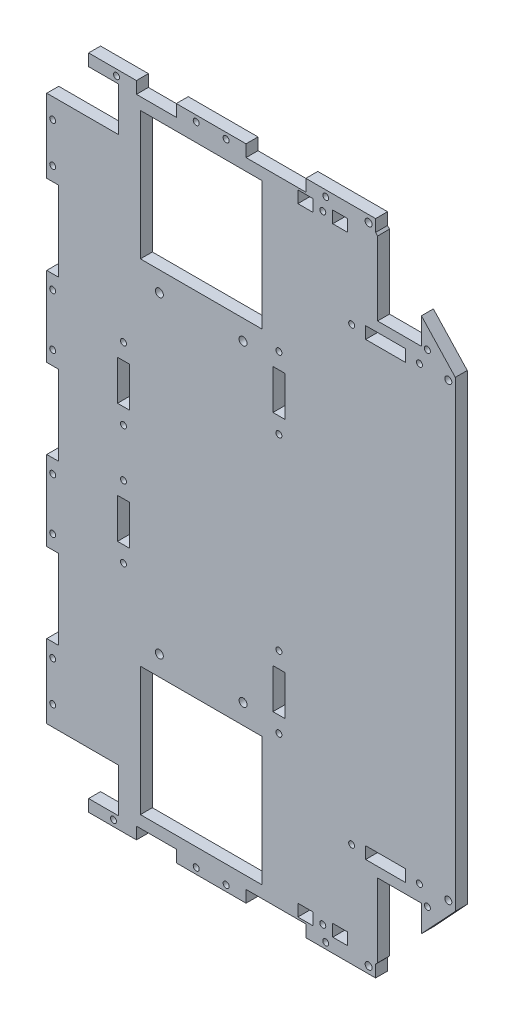
SolidWorks part; units mm, degrees
ref_plane "Plan de face" through (0, 0, 0) normal (0, 0, 1) x (1, 0, 0)
ref_plane "Plan de dessus" through (0, 0, 0) normal (0, 1, 0) x (1, 0, 0)
ref_plane "Plan de droite" through (0, 0, 0) normal (1, 0, 0) x (0, 0, -1)
sketch "Esquisse1" plane through (0, 0, 0) normal (0, 0, 1) x (1, 0, 0)
  line L1 (0, 0) -> (-205, 0)
  line L2 (0, 0) -> (0, 330)
  line L3 (0, 330) -> (-205, 330)
  line L4 (-205, 0) -> (-205, 330)
  dimension "D1" = 330
  dimension "D2" = 205
extrude "Boss.-Extru.1" add sketch "Esquisse1" along normal blind 6
sketch "Esquisse2" plane through (0, 0, 6) normal (0, 0, 1) x (1, 0, 0)
  line L0 (-205, 0) -> (0, 0) construction
  line L2 (-205, 0) -> (-156, 49) construction
  line L9 (0, 330) -> (-205, 330) construction
  line L10 (-205, 330) -> (-205, 0) construction
  line L12 (-205, 165) -> (0, 165) construction
  line L23 (0, 0) -> (0, 330) construction
  line L32 (-25, 275) -> (-45, 275)
  line L33 (-25, 275) -> (-25, 281)
  line L34 (-25, 281) -> (-45, 281)
  line L35 (-45, 275) -> (-45, 281)
  line L36 (-25, 49) -> (-45, 49)
  line L37 (-25, 49) -> (-25, 55)
  line L38 (-25, 55) -> (-45, 55)
  line L39 (-45, 49) -> (-45, 55)
  dimension "D26" = 25
  dimension "D9" = 135
  dimension "D25" = 20
  dimension "D29" = 49
  dimension "D30" = 6
  dimension "D49" = 20
  dimension "D50" = 6
  dimension "D51" = 25
  dimension "D52" = 49
extrude "roulement + encoche interne" cut sketch "Esquisse2" against normal through all
sketch "Esquisse3" plane through (0, 0, 6) normal (0, 0, 1) x (1, 0, 0)
  line L0 (0, 330) -> (-40, 330)
  line L1 (-40, 330) -> (-40, 324)
  line L2 (-40, 324) -> (0, 281)
  line L3 (-205, 0) -> (0, 0) construction
  line L4 (0, 281) -> (0, 330)
  line L5 (-40, 0) -> (-40, 6)
  line L6 (-40, 6) -> (0, 49)
  line L7 (0, 330) -> (-205, 330) construction
  line L8 (-205, 330) -> (-205, 0) construction
  line L9 (0, 0) -> (-40, 0)
  line L10 (0, 0) -> (0, 330) construction
  line L11 (0, 330) -> (-205, 330) construction
  line L12 (-75, 0) -> (-105, 0)
  line L13 (-75, 0) -> (-75, 6)
  line L14 (-205, 145) -> (-199, 145)
  line L15 (-205, 65) -> (-199, 65)
  line L16 (-205, 65) -> (-205, 105)
  line L17 (-205, 105) -> (-199, 105)
  line L18 (-199, 65) -> (-199, 105)
  line L19 (-205, 145) -> (-205, 185)
  line L20 (-205, 185) -> (-199, 185)
  line L21 (-75, 6) -> (-105, 6)
  line L22 (-105, 0) -> (-105, 6)
  line L23 (-75, 330) -> (-105, 330)
  line L24 (-75, 330) -> (-75, 324)
  line L25 (-75, 324) -> (-105, 324)
  line L26 (-105, 330) -> (-105, 324)
  line L27 (-205, 302) -> (-169, 302)
  line L28 (-199, 145) -> (-199, 185)
  line L29 (-205, 225) -> (-199, 225)
  line L30 (-205, 225) -> (-205, 265)
  line L31 (-205, 265) -> (-199, 265)
  line L32 (-199, 225) -> (-199, 265)
  line L33 (0, 49) -> (0, 0)
  line L34 (-140, 0) -> (-160, 0)
  line L35 (-140, 0) -> (-140, 6)
  line L36 (-140, 6) -> (-160, 6)
  line L37 (-205, 302) -> (-205, 330)
  line L38 (-160, 0) -> (-160, 6)
  line L39 (-140, 330) -> (-160, 330)
  line L40 (-140, 330) -> (-140, 324)
  line L41 (-140, 324) -> (-160, 324)
  line L42 (-160, 330) -> (-160, 324)
  line L43 (-184, 324) -> (-169, 324)
  line L44 (-169, 302) -> (-169, 324)
  line L46 (-205, 0) -> (-205, 28)
  line L47 (-184, 6) -> (-169, 6)
  line L49 (-205, 28) -> (-169, 28)
  line L50 (-169, 6) -> (-169, 28)
  line L51 (-205, 0) -> (-184, 0)
  line L52 (-205, 330) -> (-184, 330)
  line L54 (-184, 0) -> (-184, 6)
  line L56 (-184, 330) -> (-184, 324)
  dimension "D3" = 49
  dimension "D4" = 6
  dimension "D5" = 40
  dimension "D6" = 30
  dimension "D7" = 40
  dimension "D8" = 6
  dimension "D9" = 40
  dimension "D10" = 6
  dimension "D11" = 40
  dimension "D12" = 40
  dimension "D13" = 40
  dimension "D14" = 6
  dimension "D15" = 75
  dimension "D16" = 65
  dimension "D17" = 6
  dimension "D18" = 30
  dimension "D19" = 75
  dimension "D20" = 6
  dimension "D21" = 6
  dimension "D22" = 35
  dimension "D23" = 40
  dimension "D24" = 49
  dimension "D25" = 36
  dimension "D26" = 22
  dimension "D27" = 22
  dimension "D28" = 20
  dimension "D29" = 6
  dimension "D30" = 35
  dimension "D31" = 20
  dimension "D32" = 6
  dimension "D33" = 6
  dimension "D34" = 36
  dimension "D35" = 6
  dimension "D36" = 24
  dimension "D37" = 24
extrude "Enlèv. mat encoche" cut sketch "Esquisse3" against normal through all
sketch "Esquisse6" plane through (0, 0, 6) normal (0, 0, 1) x (1, 0, 0)
  line L0 (-199, 165) -> (0, 165) construction
  line L1 (-158, 253.5) -> (-158, 318)
  line L2 (-97, 318) -> (-97, 253.5)
  line L3 (-158, 253.5) -> (-97, 253.5)
  line L4 (-205, 225) -> (-205, 185) construction
  line L5 (-199, 145) -> (-199, 185) construction
  line L6 (0, 49) -> (0, 281) construction
  line L7 (-85.5, 90) -> (-85.5, 110)
  line L8 (-127.5, 250.9395) -> (-127.5, -49749.0605) construction
  line L9 (-40, 330) -> (-75, 330) construction
  line L10 (-158, 318) -> (-97, 318)
  line L11 (-91.5, 110) -> (-85.5, 110)
  line L12 (-91.5, 90) -> (-91.5, 110)
  line L13 (-91.5, 90) -> (-85.5, 90)
  line L14 (-163.5, 125) -> (-163.5, 145)
  line L15 (-169.5, 145) -> (-163.5, 145)
  line L16 (-169.5, 125) -> (-169.5, 145)
  line L17 (-169.5, 125) -> (-163.5, 125)
  line L18 (-158, 12) -> (-97, 12)
  line L19 (-158, 76.5) -> (-97, 76.5)
  line L20 (-97, 12) -> (-97, 76.5)
  line L21 (-158, 76.5) -> (-158, 12)
  line L22 (-169.5, 205) -> (-163.5, 205)
  line L23 (-169.5, 205) -> (-169.5, 185)
  line L24 (-169.5, 185) -> (-163.5, 185)
  line L25 (-163.5, 205) -> (-163.5, 185)
  line L26 (-91.5, 240) -> (-85.5, 240)
  line L27 (-91.5, 240) -> (-91.5, 220)
  line L28 (-91.5, 220) -> (-85.5, 220)
  line L29 (-85.5, 240) -> (-85.5, 220)
  line L30 (0, 49) -> (0, 281) construction
  line L31 (-205, 225) -> (-205, 185) construction
  line L32 (-105, 330) -> (-140, 330) construction
  circle A0 centre (-148.5, 243.5) radius 2
  circle A1 centre (-106.5, 243.5) radius 2
  circle A2 centre (-106.5, 86.5) radius 2
  circle A3 centre (-148.5, 86.5) radius 2
  point P19 (-127.5, 253.5)
  dimension "D4" = 4
  dimension "D5" = 78.5
  dimension "D6" = 64.5
  dimension "D3" = 30.5
  dimension "D7" = 42
  dimension "D8" = 10
  dimension "D9" = 77.5
  dimension "D15" = 20
  dimension "D16" = 90
  dimension "D17" = 85.5
  dimension "D18" = 6
  dimension "D19" = 20
  dimension "D20" = 6
  dimension "D21" = 35.5
  dimension "D22" = 125
extrude "bloc moteur" cut sketch "Esquisse6" against normal through all
sketch "Esquisse7" plane through (0, 0, 6) normal (0, 0, 1) x (1, 0, 0)
  line L0 (-140, 0) -> (-105, 0) construction
  line L1 (-205, 65) -> (-205, 28) construction
  line L2 (-40, 330) -> (-40, 324) construction
  line L3 (-75, 0) -> (-40, 0) construction
  line L4 (-163.5, 125) -> (-163.5, 145) construction
  line L5 (-40, 330) -> (-75, 330) construction
  line L6 (-205, 145) -> (-205, 105) construction
  line L7 (-199, 105) -> (-205, 105) construction
  line L8 (-205, 145) -> (-199, 145) construction
  line L9 (-205, 225) -> (-205, 185) construction
  line L10 (-199, 185) -> (-205, 185) construction
  line L11 (-205, 225) -> (-199, 225) construction
  line L12 (-205, 302) -> (-205, 265) construction
  line L13 (-199, 265) -> (-205, 265) construction
  line L14 (-105, 330) -> (-140, 330) construction
  line L15 (-205, 65) -> (-205, 28) construction
  line L16 (-45, 55) -> (-45, 49) construction
  line L17 (-45, 49) -> (-25, 49) construction
  line L18 (-25, 49) -> (-25, 55) construction
  line L19 (-75, 324) -> (-75, 330) construction
  line L20 (-40, 330) -> (-75, 330) construction
  line L21 (-205, 65) -> (-199, 65) construction
  line L22 (-25, 281) -> (-45, 281) construction
  line L23 (-45, 281) -> (-45, 275) construction
  line L24 (-45, 275) -> (-25, 275) construction
  line L25 (-25, 275) -> (-25, 281) construction
  line L26 (0, 49) -> (0, 281) construction
  line L27 (-45, 275) -> (-25, 275) construction
  line L28 (-45, 49) -> (-25, 49) construction
  line L29 (-75, 0) -> (-40, 0) construction
  line L30 (-40, 6) -> (-40, 0) construction
  line L31 (-75, 0) -> (-75, 6) construction
  line L32 (-85.5, 90) -> (-85.5, 110) construction
  line L33 (-199, 165) -> (0, 165) construction
  line L34 (-85.5, 110) -> (-91.5, 110) construction
  line L35 (-160, 330) -> (-160, 324) construction
  line L36 (-140, 324) -> (-140, 330) construction
  line L37 (-105, 330) -> (-105, 324) construction
  line L38 (-105, 6) -> (-105, 0) construction
  line L39 (-199, 145) -> (-199, 185) construction
  line L40 (0, 49) -> (0, 281) construction
  line L41 (-140, 0) -> (-140, 6) construction
  line L45 (-91.5, 90) -> (-85.5, 90) construction
  line L46 (-169.5, 125) -> (-163.5, 125) construction
  line L47 (-163.5, 145) -> (-169.5, 145) construction
  circle A0 centre (-65, 3) radius 1.5
  circle A1 centre (-171.5042, 3) radius 1.5
  circle A2 centre (-115, 3) radius 1.5
  circle A3 centre (-202, 58) radius 1.5
  circle A4 centre (-202, 272) radius 1.5
  circle A5 centre (-65, 327) radius 1.5
  circle A6 centre (-170, 327) radius 1.5
  circle A7 centre (-18, 52) radius 1.5
  circle A8 centre (-52, 52) radius 1.5
  circle A9 centre (-18, 278) radius 1.5
  circle A10 centre (-52, 278) radius 1.5
  circle A11 centre (-202, 112) radius 1.5
  circle A12 centre (-202, 138) radius 1.5
  circle A13 centre (-166.5, 117) radius 1.5
  circle A14 centre (-130, 327) radius 1.5
  circle A15 centre (-202, 192) radius 1.5
  circle A16 centre (-202, 218) radius 1.5
  circle A17 centre (-166.5, 153) radius 1.5
  circle A18 centre (-130, 3) radius 1.5
  circle A19 centre (-115, 327) radius 1.5
  circle A20 centre (-202, 292) radius 1.5
  circle A21 centre (-202, 38) radius 1.5
  circle A22 centre (-43.5, 326.5) radius 1.75
  circle A23 centre (-3.5, 278) radius 1.75
  circle A24 centre (-3.5, 52) radius 1.75
  circle A25 centre (-43.5, 3.5) radius 1.75
  circle A26 centre (-88.5, 82) radius 1.5
  circle A27 centre (-88.5, 118) radius 1.5
  circle A28 centre (-14, 44) radius 1.5
  circle A29 centre (-14, 286) radius 1.5
  circle A30 centre (-88.5, 212) radius 1.5
  circle A31 centre (-88.5, 248) radius 1.5
  circle A32 centre (-166.5, 177) radius 1.5
  circle A33 centre (-166.5, 213) radius 1.5
  point P71 (-25, 52)
  point P158 (-105, 3)
  dimension "D1" = 3
  dimension "D2" = 3
  dimension "D6" = 3
  dimension "D7" = 3
  dimension "D8" = 3
  dimension "D10" = 3
  dimension "D11" = 3
  dimension "D13" = 33.4958
  dimension "D14" = 3
  dimension "D15" = 10
  dimension "D16" = 3
  dimension "D17" = 3
  dimension "D18" = 7
  dimension "D19" = 3
  dimension "D20" = 3
  dimension "D21" = 7
  dimension "D22" = 3
  dimension "D23" = 3
  dimension "D24" = 7
  dimension "D25" = 3
  dimension "D26" = 3
  dimension "D27" = 7
  dimension "D28" = 3
  dimension "D29" = 3
  dimension "D30" = 7
  dimension "D31" = 3
  dimension "D32" = 3
  dimension "D33" = 7
  dimension "D34" = 10
  dimension "D35" = 3
  dimension "D36" = 3
  dimension "D37" = 3
  dimension "D38" = 7
  dimension "D39" = 3
  dimension "D40" = 3
  dimension "D41" = 3
  dimension "D42" = 7
  dimension "D43" = 3
  dimension "D44" = 10
  dimension "D45" = 3
  dimension "D46" = 3
  dimension "D47" = 3
  dimension "D48" = 8
  dimension "D49" = 3
  dimension "D50" = 10
  dimension "D51" = 3
  dimension "D52" = 3
  dimension "D53" = 3
  dimension "D55" = 3
  dimension "D56" = 3
  dimension "D57" = 7
  dimension "D58" = 3
  dimension "D59" = 20
  dimension "D60" = 3
  dimension "D61" = 3
  dimension "D62" = 10
  dimension "D63" = 3
  dimension "D64" = 3
  dimension "D65" = 20
  dimension "D66" = 3
  dimension "D67" = 3.5
  dimension "D68" = 3.5
  dimension "D69" = 3.5
  dimension "D70" = 3.5
  dimension "D71" = 3.5
  dimension "D73" = 3.5
  dimension "D74" = 3.5
  dimension "D75" = 3
  dimension "D76" = 3.5
  dimension "D77" = 3.5
  dimension "D78" = 3.5
  dimension "D79" = 3
  dimension "D81" = 3
  dimension "D82" = 3
  dimension "D84" = 3
  dimension "D85" = 3
  dimension "D86" = 8
  dimension "D87" = 3
  dimension "D88" = 3
  dimension "D89" = 14
  dimension "D91" = 3
  dimension "D90" = 5
  dimension "D92" = 14
  dimension "D93" = 5
  dimension "D80" = 8
  dimension "D83" = 8
  dimension "D94" = 10
  dimension "D12" = 10
  dimension "D54" = 7
  dimension "D72" = 3
extrude "Enlèv. mat.-Extru.4" cut sketch "Esquisse7" against normal through all
sketch "Esquisse8" plane through (0, 0, 0) normal (0, 0, -1) x (-1, 0, 0)
  line L1 (199, 165) -> (0, 165) construction
  line L4 (199, 145) -> (199, 185) construction
  line L5 (0, 49) -> (0, 281) construction
  circle A0 centre (14, 44) radius 2.995
  circle A1 centre (170, 327) radius 2.995
  circle A2 centre (202, 292) radius 2.995
  circle A3 centre (202, 272) radius 2.995
  circle A4 centre (202, 218) radius 2.995
  circle A5 centre (202, 192) radius 2.995
  circle A6 centre (130, 327) radius 2.995
  circle A7 centre (115, 327) radius 2.995
  circle A8 centre (65, 327) radius 2.995
  circle A9 centre (52, 278) radius 2.995
  circle A10 centre (18, 278) radius 2.995
  circle A11 centre (148.5, 243.5) radius 4
  circle A12 centre (106.5, 243.5) radius 4
  circle A13 centre (106.5, 86.5) radius 4
  circle A14 centre (148.5, 86.5) radius 4
  circle A15 centre (3.5, 278) radius 3.495
  circle A16 centre (52, 52) radius 2.995
  circle A17 centre (18, 52) radius 2.995
  circle A18 centre (65, 3) radius 2.995
  circle A19 centre (115, 3) radius 2.995
  circle A20 centre (130, 3) radius 2.995
  circle A21 centre (171.5042, 3) radius 2.995
  circle A22 centre (14, 286) radius 2.995
  circle A23 centre (202, 38) radius 2.995
  circle A24 centre (202, 58) radius 2.995
  circle A25 centre (202, 112) radius 2.995
  circle A26 centre (202, 138) radius 2.995
  circle A27 centre (88.5, 212) radius 3
  circle A28 centre (88.5, 248) radius 3
  circle A29 centre (166.5, 177) radius 3
  circle A30 centre (166.5, 213) radius 3
  circle A31 centre (166.5, 117) radius 3
  circle A32 centre (166.5, 153) radius 3
  circle A33 centre (88.5, 82) radius 3
  circle A34 centre (88.5, 118) radius 3
  circle A35 centre (43.5, 326.5) radius 3.495
  circle A36 centre (43.5, 3.5) radius 3.495
  circle A37 centre (3.5, 52) radius 3.495
  dimension "D1" = 5.99
  dimension "D2" = 5.99
  dimension "D3" = 5.99
  dimension "D4" = 5.99
  dimension "D5" = 5.99
  dimension "D6" = 5.99
  dimension "D7" = 5.99
  dimension "D8" = 5.99
  dimension "D9" = 5.99
  dimension "D10" = 5.99
  dimension "D11" = 5.99
  dimension "D12" = 8
  dimension "D13" = 8
  dimension "D14" = 5.99
  dimension "D15" = 6
  dimension "D16" = 6
  dimension "D17" = 6
  dimension "D18" = 6.99
  dimension "D19" = 6.99
  dimension "D20" = 6.99
  dimension "D21" = 6.99
  dimension "D22" = 6
  dimension "D23" = 5.99
extrude "Enlèv. mat.-Extru.7" cut sketch "Esquisse8" against normal blind 3
sketch "Esquisse9" plane through (0, 0, 6) normal (0, 0, 1) x (1, 0, 0)
  line L0 (0, 49) -> (-40, 6) construction
  line L1 (-17, 44) -> (-39, 44)
  line L2 (-17, 44) -> (-17, 7.075)
  line L3 (-17, 7.075) -> (-39, 7.075)
  line L4 (-39, 44) -> (-39, 7.075)
  line L6 (-75, 6) -> (-105, 6) construction
  line L7 (-79, 13) -> (-71.5, 13)
  line L8 (-79, 13) -> (-79, 7)
  line L9 (-79, 7) -> (-71.5, 7)
  line L11 (-45, 49) -> (-25, 49) construction
  line L12 (-71.5, 13) -> (-71.5, 7)
  line L13 (-61.5, 13) -> (-54, 13)
  line L14 (-199, 165) -> (0, 165) construction
  line L15 (-61.5, 13) -> (-61.5, 7)
  line L16 (-61.5, 7) -> (-54, 7)
  line L17 (-199, 145) -> (-199, 185) construction
  line L18 (0, 49) -> (0, 281) construction
  line L19 (-54, 13) -> (-54, 7)
  line L20 (-75, 0) -> (-40, 0) construction
  line L21 (-54, 317) -> (-54, 323)
  line L22 (-61.5, 323) -> (-54, 323)
  line L23 (-61.5, 317) -> (-61.5, 323)
  line L24 (-61.5, 317) -> (-54, 317)
  line L25 (-71.5, 317) -> (-71.5, 323)
  line L26 (-79, 323) -> (-71.5, 323)
  line L27 (-79, 317) -> (-79, 323)
  line L28 (-79, 317) -> (-71.5, 317)
  line L29 (-39, 286) -> (-39, 322.925)
  line L30 (-17, 322.925) -> (-39, 322.925)
  line L31 (-17, 286) -> (-17, 322.925)
  line L32 (-17, 286) -> (-39, 286)
  circle A0 centre (-66.5, 10) radius 1.5
  circle A1 centre (-66.5, 320) radius 1.5
  circle A5 centre (-14, 44) radius 1.5 construction
  dimension "D11" = 13
  dimension "D9" = 1
  dimension "D12" = 3
  dimension "D13" = 5
  dimension "D14" = 3
  dimension "D1" = 6
  dimension "D2" = 6
  dimension "D3" = 7.5
  dimension "D4" = 7.5
  dimension "D5" = 10
  dimension "D6" = 22
  dimension "D7" = 5
  dimension "D8" = 15
  dimension "D10" = 3
extrude "Enlèv. mat.-Extru.8" cut sketch "Esquisse9" against normal through all
sketch "Esquisse10" plane through (0, 0, 0) normal (0, 0, -1) x (-1, 0, 0)
  circle A0 centre (66.5, 320) radius 2.995
  circle A1 centre (66.5, 10) radius 2.995
  dimension "D1" = 5.99
  dimension "D2" = 5.99
extrude "Enlèv. mat.-Extru.9" cut sketch "Esquisse10" against normal blind 3
